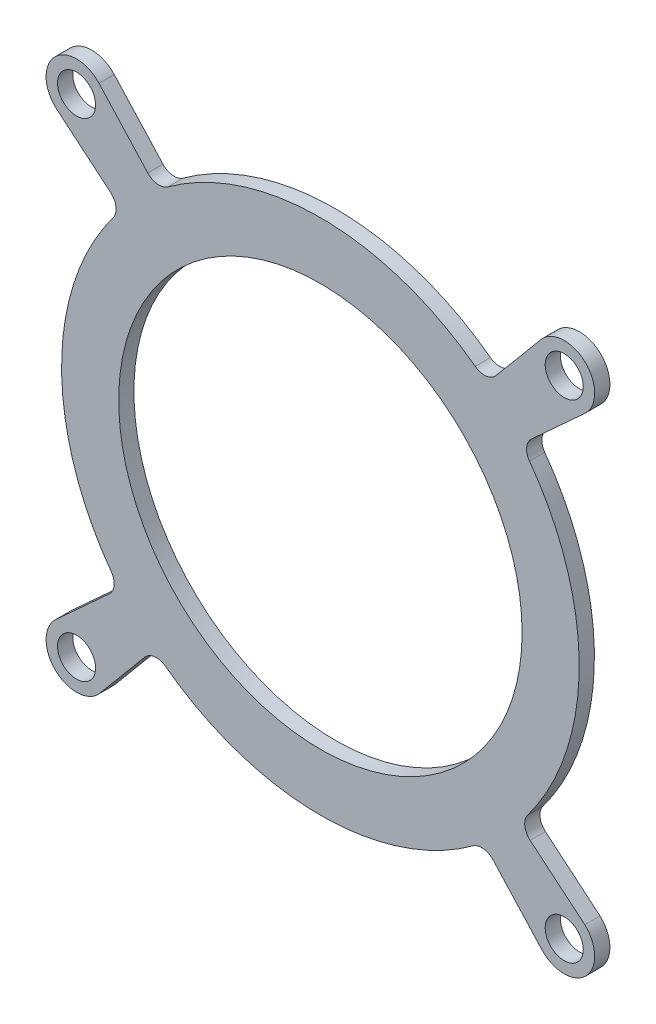
SolidWorks part; units mm, degrees
ref_plane "前视基准面" through (0, 0, 0) normal (0, 0, 1) x (1, 0, 0)
ref_plane "上视基准面" through (0, 0, 0) normal (0, 1, 0) x (1, 0, 0)
ref_plane "右视基准面" through (0, 0, 0) normal (1, 0, 0) x (0, 0, -1)
sketch "草图1" plane through (0, 0, 0) normal (0, 0, 1) x (1, 0, 0)
  line L0 (0, 0.4371) -> (28.5, 0.4371) construction
  line L105 (29.0849, -34.2991) -> (22.6815, -27.3036)
  line L106 (-34.7363, -28.6478) -> (-27.7408, -22.2444)
  line L107 (34.7363, -28.6478) -> (27.5593, -22.6385)
  line L108 (-29.0849, -34.2991) -> (-23.0756, -27.1222)
  line L109 (-29.0849, 35.1734) -> (-22.6815, 28.1779)
  line L110 (-34.7363, 29.5221) -> (-27.5593, 23.5128)
  line L111 (34.7363, 29.5221) -> (27.7408, 23.1186)
  line L112 (29.0849, 35.1734) -> (23.0756, 27.9965)
  circle A0 centre (0, 0.4371) radius 34 construction
  circle A150 centre (0, 0.4371) radius 45.305 construction
  circle A151 centre (32.0355, -31.5983) radius 2.5
  circle A152 centre (32.0355, -31.5983) radius 4 construction
  arc A153 (29.0849, -34.2991) -> (34.7363, -28.6478) centre (32.0355, -31.5983) ccw
  arc A154 (-34.7363, -28.6478) -> (-29.0849, -34.2991) centre (-32.0355, -31.5983) ccw
  circle A155 centre (-32.0355, -31.5983) radius 2.5
  arc A156 (-29.0849, 35.1734) -> (-34.7363, 29.5221) centre (-32.0355, 32.4726) ccw
  circle A157 centre (-32.0355, 32.4726) radius 2.5
  arc A158 (34.7363, 29.5221) -> (29.0849, 35.1734) centre (32.0355, 32.4726) ccw
  circle A159 centre (32.0355, 32.4726) radius 2.5
  arc A160 (-20.3454, -26.8037) -> (20.0281, -27.0378) centre (0, 0.4371) ccw
  arc A161 (27.2409, -19.9082) -> (27.475, 20.4653) centre (0, 0.4371) ccw
  arc A162 (20.3454, 27.678) -> (-20.0281, 27.9121) centre (0, 0.4371) ccw
  arc A163 (-27.2409, 20.7825) -> (-27.475, -19.591) centre (0, 0.4371) ccw
  arc A164 (-23.0756, -27.1222) -> (-20.3454, -26.8037) centre (-21.5422, -28.4061) cw
  arc A165 (22.6815, -27.3036) -> (20.0281, -27.0378) centre (21.2062, -28.654) ccw
  arc A166 (27.5593, -22.6385) -> (27.2409, -19.9082) centre (28.8433, -21.105) cw
  arc A167 (27.7408, 23.1186) -> (27.475, 20.4653) centre (29.0912, 21.6434) ccw
  arc A168 (23.0756, 27.9965) -> (20.3454, 27.678) centre (21.5422, 29.2804) cw
  arc A169 (-22.6815, 28.1779) -> (-20.0281, 27.9121) centre (-21.2062, 29.5283) ccw
  arc A170 (-27.5593, 23.5128) -> (-27.2409, 20.7825) centre (-28.8433, 21.9793) cw
  arc A171 (-27.7408, -22.2444) -> (-27.475, -19.591) centre (-29.0912, -20.7691) ccw
  circle A172 centre (0, 0.4371) radius 26.5
extrude "凸台-拉伸1" add sketch "草图1" along normal blind 2
